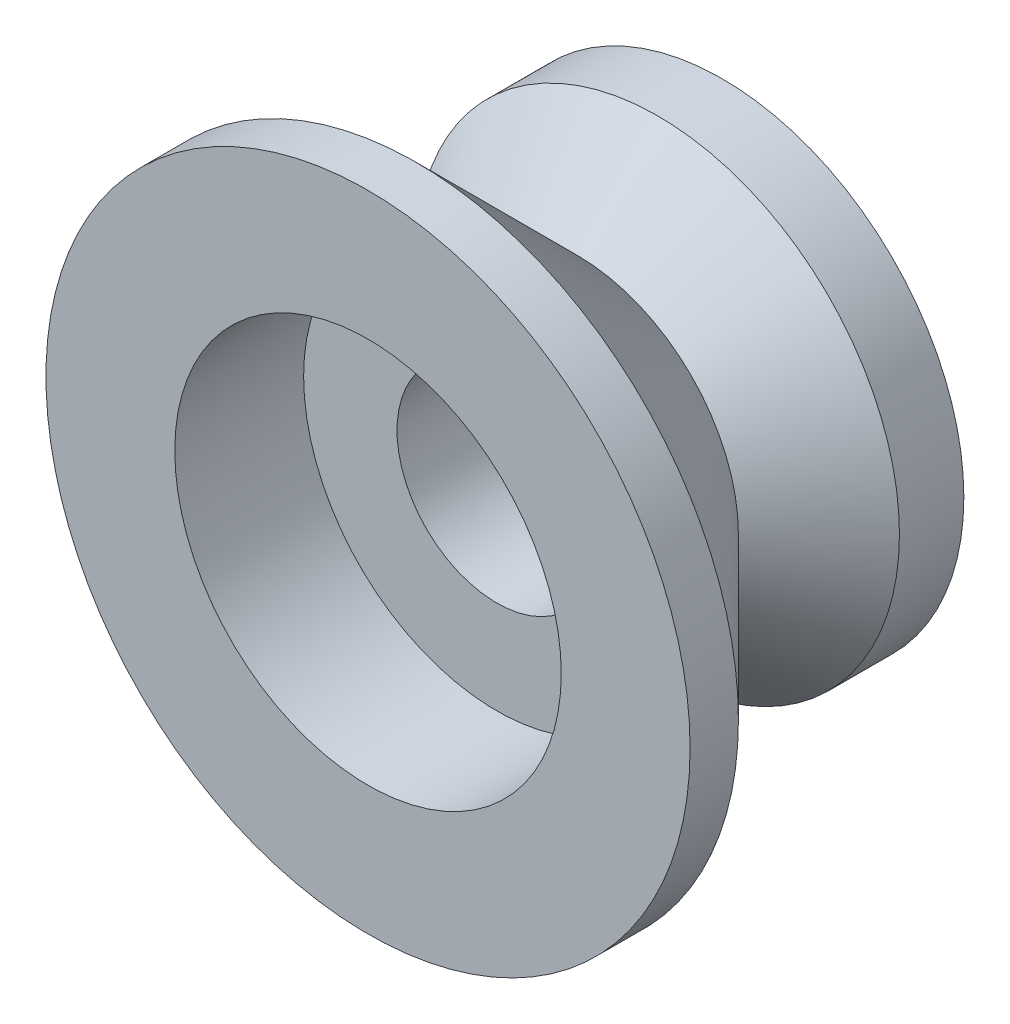
SolidWorks part; units mm, degrees
ref_plane "Front Plane" through (0, 0, 0) normal (0, 0, 1) x (1, 0, 0)
ref_plane "Top Plane" through (0, 0, 0) normal (0, 1, 0) x (1, 0, 0)
ref_plane "Right Plane" through (0, 0, 0) normal (1, 0, 0) x (0, 0, -1)
sketch "草图1" plane through (0, 0, 0) normal (0, 1, 0) x (1, 0, 0)
  line L0 (0, -1000) -> (0, 49000) construction
  line L1 (-7.5, 9) -> (-5, 6.5)
  line L2 (-5, 6.5) -> (-7.5, 4)
  line L3 (-7.5, 4) -> (-10, 4) construction
  line L4 (-10, 4) -> (-10, 0) construction
  line L7 (-7.5, 9) -> (-7.5, 11)
  line L13 (-10, 0) -> (0, 0)
  line L14 (-7.5, 11) -> (0, 11)
  line L15 (0, 0) -> (0, 11)
  line L16 (-7.5, 4) -> (-10, 1.5)
  line L17 (-10, 1.5) -> (-10, 0)
  point P10 (0, 11)
  point P13 (0, 0)
  dimension "D1" = 10
  dimension "D2" = 2.5
  dimension "D3" = 5
  dimension "D4" = 4
  dimension "D5" = 2
  dimension "D6" = 135
revolve "旋转1" add sketch "草图1" angle 360 about L0
sketch "草图2" plane through (0, 0, 0) normal (0, 0, 1) x (1, 0, 0)
  circle A0 centre (0, 0) radius 6
  dimension "D1" = 12
extrude "切除-拉伸1" cut sketch "草图2" against normal blind 4
sketch "草图3" plane through (0, 0, -4) normal (0, 0, 1) x (1, 0, 0)
  circle A0 centre (0, 0) radius 3.1
  dimension "D1" = 6.2
extrude "切除-拉伸2" cut sketch "草图3" against normal through all
